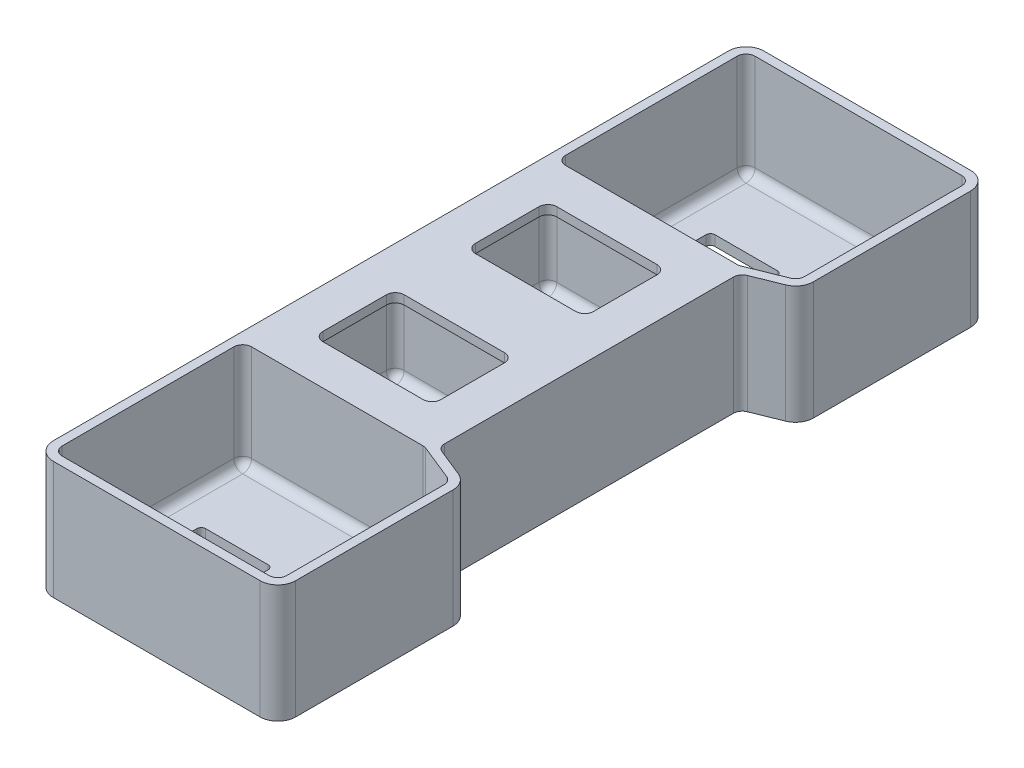
SolidWorks part; units mm, degrees
ref_plane "前视基准面" through (0, 0, 0) normal (0, 0, 1) x (1, 0, 0)
ref_plane "上视基准面" through (0, 0, 0) normal (0, 1, 0) x (1, 0, 0)
ref_plane "右视基准面" through (0, 0, 0) normal (1, 0, 0) x (0, 0, -1)
other "Configuration Table"
sketch "草图1" plane through (0, 0, 0) normal (0, 1, 0) x (1, 0, 0)
  line L0 (0, 0) -> (1158.6996, 0) construction
  line L1 (0, -797.5) -> (0, 797.5)
  line L2 (0, 797.5) -> (544, 797.5)
  line L3 (544, 797.5) -> (544, 377.5)
  line L4 (544, 377.5) -> (445, 337.5)
  line L5 (445, 337.5) -> (445, -337.5)
  line L6 (20, 10) -> (425, 10)
  line L7 (425, 10) -> (425, 332.5)
  line L8 (425, 332.5) -> (20, 332.5)
  line L9 (20, 332.5) -> (20, 10)
  line L10 (20, 777.5) -> (20, 352.5)
  line L11 (20, 352.5) -> (428.7373, 352.5)
  line L12 (428.7373, 352.5) -> (524, 390.99)
  line L13 (524, 390.99) -> (524, 777.5)
  line L14 (524, 777.5) -> (20, 777.5)
  line L15 (524, -777.5) -> (20, -777.5)
  line L16 (524, -390.99) -> (524, -777.5)
  line L17 (428.7373, -352.5) -> (524, -390.99)
  line L18 (20, -352.5) -> (428.7373, -352.5)
  line L19 (20, -777.5) -> (20, -352.5)
  line L20 (20, -332.5) -> (20, -10)
  line L21 (425, -332.5) -> (20, -332.5)
  line L22 (425, -10) -> (425, -332.5)
  line L23 (20, -10) -> (425, -10)
  line L24 (544, -377.5) -> (445, -337.5)
  line L25 (544, -797.5) -> (544, -377.5)
  line L26 (0, -797.5) -> (544, -797.5)
  point P30 (445, 0)
  dimension "D1" = 1595
  dimension "D2" = 544
  dimension "D3" = 420
  dimension "D4" = 460
  dimension "D5" = 445
  dimension "D6" = 20
  dimension "D7" = 20
  dimension "D8" = 20
  dimension "D9" = 20
  dimension "D10" = 20
  dimension "D11" = 20
  dimension "D12" = 20
  dimension "D13" = 20
  dimension "D14" = 425
extrude "凸台-拉伸1" add sketch "草图1" along normal blind 265
sketch "草图2" plane through (0, 0, -797.5) normal (0, 0, -1) x (-1, 0, 0)
  line L0 (-544, 28) -> (0, 28)
  line L1 (-544, 265) -> (-544, 0) construction
  line L2 (0, 265) -> (0, 0) construction
  line L3 (0, 28) -> (0, 5)
  line L4 (0, 5) -> (-544, 5)
  line L5 (-544, 5) -> (-544, 28)
  line L6 (-544, 0) -> (0, 0) construction
  dimension "D1" = 23
  dimension "D2" = 5
extrude "凸台-拉伸2" add sketch "草图2" against normal up to surface (1595 mm away) up to face at (272, 132.5, 797.5)
sketch "草图3" plane through (0, 28, 0) normal (0, 1, 0) x (1, 0, 0)
  line L0 (544, -377.5) -> (544, 377.5) construction
  line L1 (544, -377.5) -> (445, -337.5) construction
  line L2 (445, -337.5) -> (445, 337.5) construction
  line L3 (445, 337.5) -> (544, 377.5) construction
  line L4 (544, -377.5) -> (544, 377.5)
  line L5 (544, -377.5) -> (445, -337.5)
  line L6 (445, -337.5) -> (445, 337.5)
  line L7 (445, 337.5) -> (544, 377.5)
extrude "切除-拉伸1" cut sketch "草图3" against normal blind 265
sketch "草图4" plane through (0, 28, 0) normal (0, 1, 0) x (1, 0, 0)
  line L0 (95, 612.5) -> (95, 530.5)
  line L1 (105, 520.5) -> (245, 520.5)
  line L2 (255, 530.5) -> (255, 612.5)
  line L3 (105, 622.5) -> (245, 622.5)
  line L4 (524, 777.5) -> (20, 777.5) construction
  line L5 (20, 777.5) -> (20, 352.5) construction
  line L6 (0, 0) -> (743.9678, 0) construction
  line L7 (95, -612.5) -> (95, -530.5)
  line L8 (105, -520.5) -> (245, -520.5)
  line L9 (255, -530.5) -> (255, -612.5)
  line L10 (105, -622.5) -> (245, -622.5)
  arc A0 (245, 520.5) -> (255, 530.5) centre (245, 530.5) ccw
  arc A1 (255, 612.5) -> (245, 622.5) centre (245, 612.5) ccw
  arc A2 (105, 520.5) -> (95, 530.5) centre (105, 530.5) cw
  arc A3 (95, 612.5) -> (105, 622.5) centre (105, 612.5) cw
  arc A4 (105, -520.5) -> (95, -530.5) centre (105, -530.5) ccw
  arc A5 (245, -520.5) -> (255, -530.5) centre (245, -530.5) cw
  arc A6 (255, -612.5) -> (245, -622.5) centre (245, -612.5) cw
  arc A7 (95, -612.5) -> (105, -622.5) centre (105, -612.5) ccw
  point P12 (255, 622.5)
  point P15 (95, 520.5)
  point P18 (95, 622.5)
  dimension "D5" = 10
  dimension "D1" = 155
  dimension "D2" = 160
  dimension "D3" = 102
  dimension "D4" = 75
extrude "切除-拉伸2" cut sketch "草图4" against normal up to surface (23 mm away) up to face at (303.3475, 5, 530.198)
sketch "草图5" plane through (0, 28, 0) normal (0, 1, 0) x (1, 0, 0)
  line L0 (292, 704.5) -> (292, 450.5)
  line L1 (300, 442.5) -> (488, 442.5)
  line L2 (496, 450.5) -> (496, 704.5)
  line L3 (488, 712.5) -> (300, 712.5)
  line L4 (292, 712.5) -> (496, 442.5) construction
  line L5 (524, 777.5) -> (20, 777.5) construction
  line L6 (524, 390.99) -> (524, 777.5) construction
  line L9 (0, 0) -> (866.175, 0) construction
  line L10 (496, -450.5) -> (496, -704.5)
  line L11 (300, -442.5) -> (488, -442.5)
  line L12 (292, -704.5) -> (292, -450.5)
  line L13 (488, -712.5) -> (300, -712.5)
  circle A0 centre (394, 577.5) radius 77
  arc A1 (300, 442.5) -> (292, 450.5) centre (300, 450.5) cw
  arc A2 (488, 442.5) -> (496, 450.5) centre (488, 450.5) ccw
  arc A3 (496, 704.5) -> (488, 712.5) centre (488, 704.5) ccw
  arc A4 (300, 712.5) -> (292, 704.5) centre (300, 704.5) ccw
  circle A5 centre (394, -577.5) radius 77
  arc A6 (488, -442.5) -> (496, -450.5) centre (488, -450.5) cw
  arc A7 (300, -442.5) -> (292, -450.5) centre (300, -450.5) ccw
  arc A8 (496, -704.5) -> (488, -712.5) centre (488, -704.5) cw
  arc A9 (300, -712.5) -> (292, -704.5) centre (300, -704.5) cw
  point P13 (292, 442.5)
  point P19 (496, 712.5)
  dimension "D3" = 154
  dimension "D6" = 8
  dimension "D1" = 270
  dimension "D2" = 204
  dimension "D4" = 200
  dimension "D5" = 28
extrude "切除-拉伸3" cut sketch "草图5" against normal blind 3
sketch "草图6" plane through (0, 28, 0) normal (0, 1, 0) x (1, 0, 0)
  circle A0 centre (394, -577.5) radius 77 construction
  circle A1 centre (394, 577.5) radius 77
  circle A3 centre (394, 577.5) radius 77
  circle A4 centre (394, -577.5) radius 77
  dimension "D1" = 0
extrude "切除-拉伸4" cut sketch "草图6" against normal up to surface (23 mm away) up to face at (303.3475, 5, -530.198)
sketch "草图7" plane through (0, 0, -352.5) normal (0, 0, -1) x (-1, 0, 0)
  line L0 (-428.7373, 265) -> (-428.7373, 245)
  line L1 (-428.7373, 245) -> (0, 245)
  line L2 (0, 265) -> (0, 0) construction
  line L3 (0, 245) -> (0, 265)
  line L4 (0, 265) -> (-428.7373, 265)
  dimension "D1" = 20
extrude "凸台-拉伸3" add sketch "草图7" against normal up to surface (685 mm away) up to face at (222.5, 146.5, 332.5)
sketch "草图8" plane through (0, 265, 0) normal (0, 1, 0) x (1, 0, 0)
  line L0 (0, 0) -> (893.3595, 0) construction
  line L1 (90, 242.5) -> (90, 100)
  line L2 (110, 80) -> (335, 80)
  line L3 (355, 100) -> (355, 242.5)
  line L4 (335, 262.5) -> (110, 262.5)
  line L5 (0, 797.5) -> (0, -797.5) construction
  line L7 (355, -100) -> (355, -242.5)
  line L8 (110, -80) -> (335, -80)
  line L9 (90, -242.5) -> (90, -100)
  line L10 (335, -262.5) -> (110, -262.5)
  arc A0 (335, 262.5) -> (355, 242.5) centre (335, 242.5) cw
  arc A1 (110, 262.5) -> (90, 242.5) centre (110, 242.5) ccw
  arc A2 (335, 80) -> (355, 100) centre (335, 100) ccw
  arc A3 (110, 80) -> (90, 100) centre (110, 100) cw
  arc A4 (335, -80) -> (355, -100) centre (335, -100) cw
  arc A5 (110, -80) -> (90, -100) centre (110, -100) ccw
  arc A6 (335, -262.5) -> (355, -242.5) centre (335, -242.5) ccw
  arc A7 (110, -262.5) -> (90, -242.5) centre (110, -242.5) cw
  point P9 (222.5, 80)
  point P12 (355, 262.5)
  point P15 (90, 262.5)
  dimension "D5" = 20
  dimension "D6" = 20
  dimension "D1" = 90
  dimension "D2" = 265
  dimension "D3" = 182.5
  dimension "D4" = 80
extrude "切除-拉伸5" cut sketch "草图8" against normal blind 20
sketch "草图9" plane through (0, 25, 0) normal (0, 1, 0) x (1, 0, 0)
  line L0 (394, 712.5) -> (394, 577.5) construction
  line L1 (488, 712.5) -> (300, 712.5) construction
  line L2 (394, 577.5) -> (509.1213, 577.5) construction
  line L3 (0, 0) -> (577.0376, 0) construction
  circle A0 centre (474, 692.5) radius 5
  circle A1 centre (314, 692.5) radius 5
  circle A2 centre (474, 462.5) radius 5
  circle A3 centre (314, 462.5) radius 5
  circle A4 centre (314, -462.5) radius 5
  circle A5 centre (474, -462.5) radius 5
  circle A6 centre (474, -692.5) radius 5
  circle A7 centre (314, -462.5) radius 5
  circle A8 centre (314, -462.5) radius 5
  circle A9 centre (314, -462.5) radius 5
  point P5 (474, 692.5)
  point P7 (314, 692.5)
  point P10 (474, 462.5)
  point P12 (314, 462.5)
  point P17 (314, -462.5)
  point P19 (474, -462.5)
  point P21 (474, -692.5)
  point P23 (314, -692.5)
  point P41 (314, -692.5)
  dimension "D1" = 10
  dimension "D2" = 80
  dimension "D3" = 230
hole_wizard "M10 螺纹孔1" positions "草图9" profile "草图10" tap size "M10" standard "GB"
sketch "草图10" plane through (314, 25, 692.5) normal (1, 0, 0) x (0, 0, 1)
  line L0 (0, 0) -> (0, 22.5537)
  line L1 (0, 22.5537) -> (4.25, 20)
  line L2 (4.25, 20) -> (4.25, 0.775)
  line L3 (4.25, 0.775) -> (5.025, 0)
  line L5 (5.025, 0) -> (0, 0)
  line L6 (-4.25, 0.775) -> (-5.025, 0) construction
  line L10 (0, 22.5537) -> (-4.25, 20) construction
  line L11 (0, -6.35) -> (0, 107.95) construction
  dimension "螺纹孔钻头直径" = 8.5
  dimension "螺纹孔钻头深度" = 20
  dimension "近端锥形沉头孔直径" = 10.05
  dimension "近端锥形沉头孔角度" = 90
  dimension "导头角度" = 118
cosmetic thread "孔螺纹线1" parameters "D1"=20, "D2"=10
cosmetic thread "孔螺纹线2" parameters "D1"=20, "D2"=10
cosmetic thread "孔螺纹线3" parameters "D1"=20, "D2"=10
cosmetic thread "孔螺纹线4" parameters "D1"=20, "D2"=10
cosmetic thread "孔螺纹线5" parameters "D1"=20, "D2"=10
cosmetic thread "孔螺纹线6" parameters "D1"=20, "D2"=10
cosmetic thread "孔螺纹线7" parameters "D1"=20, "D2"=10
cosmetic thread "孔螺纹线8" parameters "D1"=20, "D2"=10
cosmetic thread "孔螺纹线9" parameters "D1"=20, "D2"=10
sketch "草图11" plane through (0, 0, -352.5) normal (0, 0, -1) x (-1, 0, 0)
  line L0 (-20, 0) -> (-428.7373, 0) construction
  line L1 (-428.7373, 5) -> (-20, 5) construction
  line L2 (-20, 0) -> (-428.7373, 0)
  line L3 (-428.7373, 5) -> (-20, 5)
  line L4 (-428.7373, 5) -> (-428.7373, 0)
  line L5 (-20, 5) -> (-20, 0)
extrude "切除-拉伸6" cut sketch "草图11" against normal up to surface (705 mm away)
fillet "圆角1" radius 20 6 edges at (20, 146.5, -352.5) (428.7373, 146.5, -352.5) (524, 146.5, -390.99) (524, 146.5, -777.5) (20, 146.5, -777.5) (445, 132.5, -337.5)
fillet "圆角2" radius 40 3 edges at (544, 132.5, -377.5) (544, 132.5, -797.5) (0, 132.5, -797.5)
fillet "圆角3" radius 20 6 edges at (445, 132.5, 337.5) (524, 146.5, 777.5) (428.7373, 146.5, 352.5) (524, 146.5, 390.99) (20, 146.5, 352.5) (20, 146.5, 777.5)
fillet "圆角4" radius 40 3 edges at (544, 132.5, 377.5) (544, 132.5, 797.5) (0, 132.5, 797.5)
fillet "圆角5" radius 20 8 edges at (425, 136.5, 332.5) (20, 136.5, 332.5) (20, 136.5, 10) (425, 136.5, 10) (20, 136.5, -10) (20, 136.5, -332.5) (425, 136.5, -10) (425, 136.5, -332.5)
fillet "圆角6" radius 20 36 edges at (25.8579, 28, -326.6421) (222.5, 28, -332.5) (419.1421, 28, -326.6421) (425, 28, -171.25) (419.1421, 28, -15.8579) (222.5, 28, -10) (25.8579, 28, -15.8579) (25.8579, 28, 15.8579) (222.5, 28, 10) (419.1421, 28, 15.8579) (425, 28, 171.25) (419.1421, 28, 326.6421) (222.5, 28, 332.5) (25.8579, 28, 326.6421) (25.8579, 28, -771.6421) (272, 28, -777.5) (518.1421, 28, -771.6421) (524, 28, -580.99) (520.5808, 28, -393.2962) (471.9171, 28, -369.9464) (428.6658, 28, -352.8675) (232.4248, 28, -352.5) (25.8579, 28, -358.3579) (25.8579, 28, 358.3579) (232.4248, 28, 352.5) (428.6658, 28, 352.8675) (471.9171, 28, 369.9464) (520.5808, 28, 393.2962) (524, 28, 580.99) (518.1421, 28, 771.6421) (272, 28, 777.5) (25.8579, 28, 771.6421) (20, 28, -171.25) (20, 28, 171.25) (20, 28, -565) (20, 28, 565)
fillet "圆角7" radius 20 8 edges at (428.7373, 2.5, 352.5) (524, 2.5, 390.99) (524, 2.5, -390.99) (524, 2.5, -777.5) (428.7373, 2.5, -352.5) (20, 2.5, -777.5) (20, 2.5, 777.5) (524, 2.5, 777.5)
fillet "圆角8" radius 20 16 edges at (419.1421, 245, -326.6421) (222.5, 245, -332.5) (25.8579, 245, -326.6421) (20, 245, -171.25) (25.8579, 245, -15.8579) (222.5, 245, -10) (419.1421, 245, -15.8579) (419.1421, 245, 15.8579) (222.5, 245, 10) (25.8579, 245, 15.8579) (20, 245, 171.25) (25.8579, 245, 326.6421) (222.5, 245, 332.5) (419.1421, 245, 326.6421) (425, 245, -171.25) (425, 245, 171.25)
